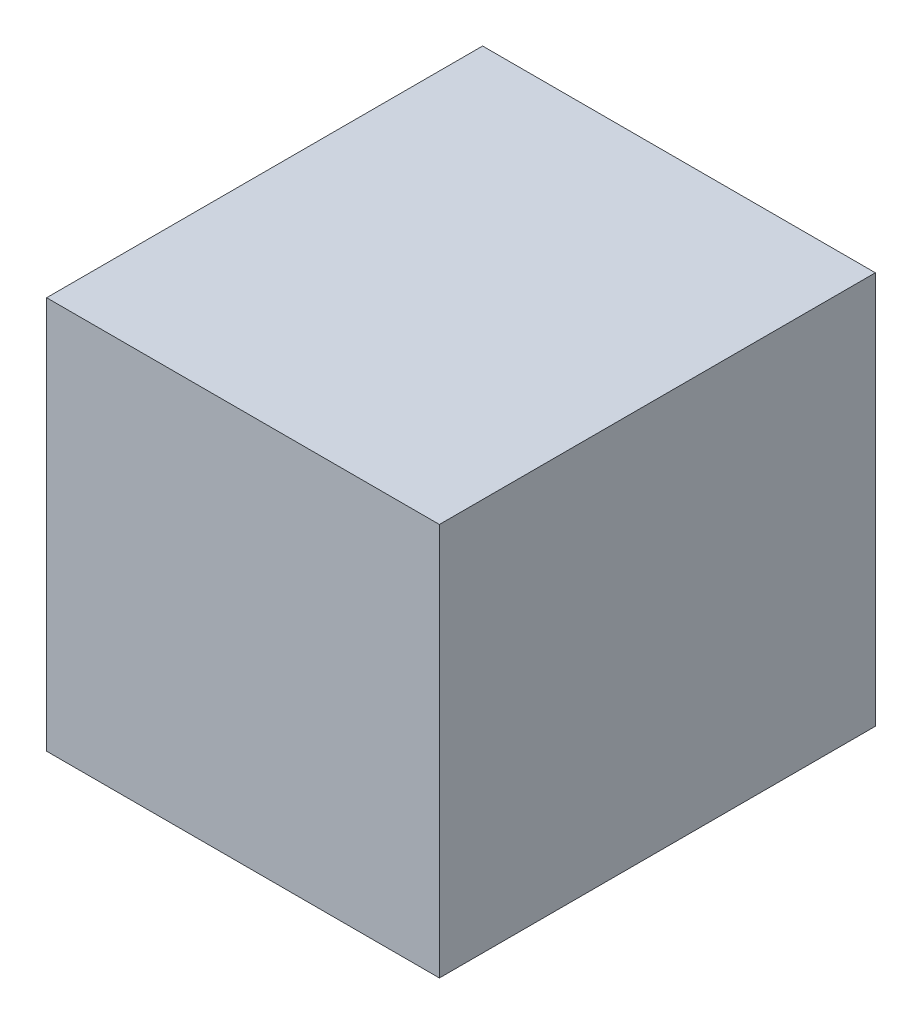
SolidWorks part; units mm, degrees
material "聚脂树脂"
ref_plane "前视基准面" through (0, 0, 0) normal (0, 0, 1) x (1, 0, 0)
ref_plane "上视基准面" through (0, 0, 0) normal (0, 1, 0) x (1, 0, 0)
ref_plane "右视基准面" through (0, 0, 0) normal (1, 0, 0) x (0, 0, -1)
other "Configuration Table"
sketch "草图1" plane through (0, 0, 0) normal (0, 1, 0) x (1, 0, 0)
  line L1 (-5, -5.55) -> (5, -5.55)
  line L2 (-5, -5.55) -> (-5, 5.55)
  line L3 (-5, 5.55) -> (5, 5.55)
  line L4 (5, -5.55) -> (5, 5.55)
  line L5 (-5, -5.55) -> (5, 5.55) construction
  line L6 (-5, 5.55) -> (5, -5.55) construction
  point P0 (0, 0)
  dimension "D1" = 10
  dimension "D2" = 11.1
extrude "凸台-拉伸1" add sketch "草图1" along normal blind 10
